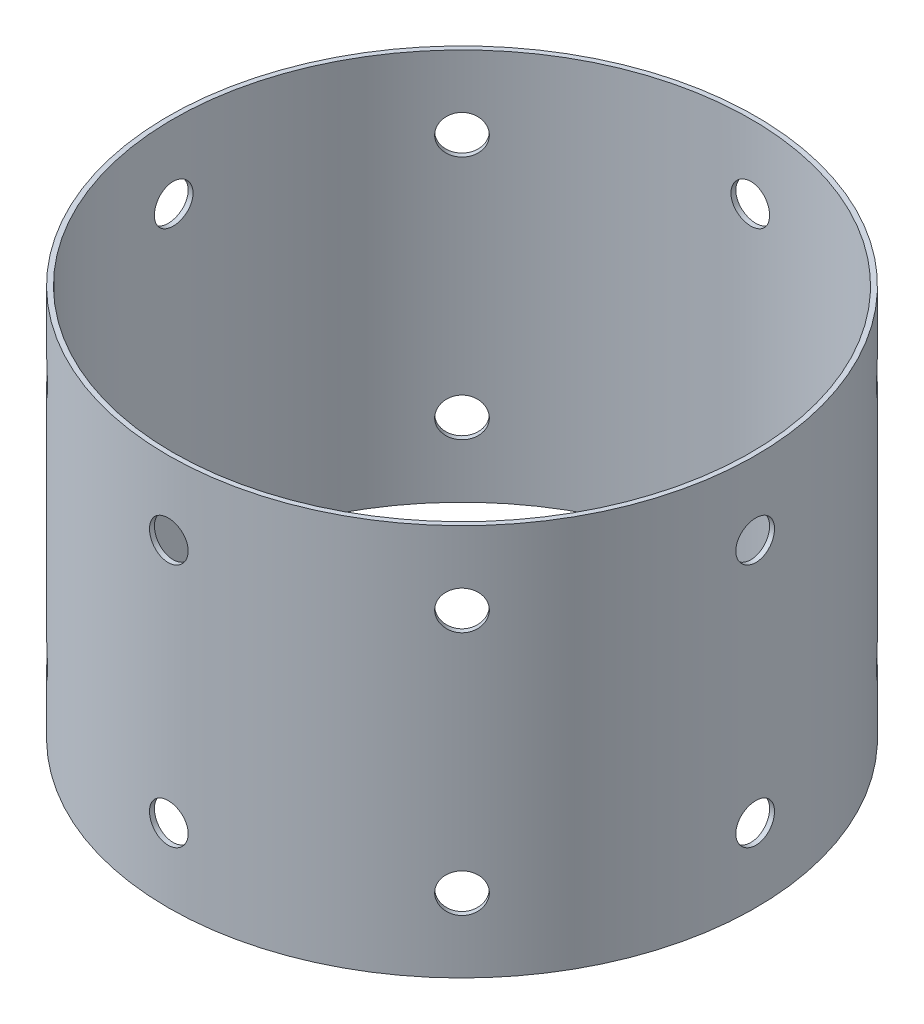
SolidWorks part; units mm, degrees
material "6061-T6 (SS)"
ref_plane "Front Plane" through (0, 0, 0) normal (0, 0, 1) x (1, 0, 0)
ref_plane "Top Plane" through (0, 0, 0) normal (0, 1, 0) x (1, 0, 0)
ref_plane "Right Plane" through (0, 0, 0) normal (1, 0, 0) x (0, 0, -1)
sketch "Sketch2" plane through (0, 0, 0) normal (0, 1, 0) x (1, 0, 0)
  circle A0 centre (0, 0) radius 74.93
  circle A1 centre (0, 0) radius 76.2
  dimension "D1" = 152.4
  dimension "D2" = 1.27
extrude "Boss-Extrude1" add sketch "Sketch2" along normal blind 101.6
sketch "Sketch3" plane through (0, 127, 0) normal (1, 0, 0) x (0, 0, -1)
  circle A0 centre (0, -44.45) radius 4.7625 construction
  circle A1 centre (0, -44.45) radius 4.7625 construction
  circle A2 centre (0, -44.45) radius 5.0165
  dimension "D1" = 0.254
extrude "LOX to Kero, LOX Side Holes" cut sketch "Sketch3" along normal up to surface (76.0347 mm away)
pattern_circular "CirPattern1" count 8 over 360 about axis through (0, 101.6, 0) along (0, 1, 0) of "LOX to Kero, LOX Side Holes"
sketch "Sketch4" plane through (0, -25.4, 0) normal (1, 0, 0) x (0, 0, 1)
  circle A0 centre (0, -44.45) radius 4.7625 construction
  circle A1 centre (0, -44.45) radius 4.7625 construction
  circle A2 centre (0, -44.45) radius 5.0165
  dimension "D1" = 0.254
extrude "LOX to Kero, Kero Side Holes" cut sketch "Sketch4" along normal up to surface (76.0347 mm away)
pattern_circular "CirPattern2" count 8 over 360 about axis through (0, 0, 0) along (0, 1, 0) of "LOX to Kero, Kero Side Holes"
sketch "Sketch5" [suppressed] plane through (0, -25.4, 0) normal (1, 0, 0) x (0, 0, 1)
  circle A0 centre (0, -44.45) radius 4.7625 construction
  circle A1 centre (0, -44.45) radius 4.7625 construction
  circle A2 centre (0, -44.45) radius 5.0165
  dimension "D1" = 0.254
extrude "N2 to LOX, LOX Side Holes" [suppressed] cut sketch "Sketch5" along normal up to surface (78.1983 mm away)
pattern_circular "CirPattern3" [suppressed] count 8 over 360
sketch "Sketch7" [suppressed] plane through (0, 0, 0) normal (1, 0, 0) x (0, 0, -1)
  line L0 (-2.3812, 327.3303) -> (2.3812, 327.3303) construction
  line L1 (0, 329.7115) -> (0, 324.949) construction
  line L2 (-2.3812, 604.52) -> (2.3812, 604.52) construction
  line L4 (0, 606.9012) -> (0, 602.1388) construction
  circle A0 centre (0, 604.52) radius 2.3812
  circle A2 centre (0, 327.3303) radius 2.3785
  spline S1 degree 3 poles (-2.3812, 327.3303) (-2.3812, 326.701) (-2.123, 326.0856) (-1.2443, 325.207) (-0.6225, 324.9494) (0.62, 324.9487) (1.2382, 325.2013) (2.1277, 326.0899) (2.381, 326.7078) (2.3815, 327.9511) (2.1241, 328.5729) (1.2467, 329.452) (0.6306, 329.7109) (-0.6258, 329.7122) (-1.2425, 329.4547) (-2.1225, 328.5761) (-2.3813, 327.9596) (-2.3812, 327.3303) (-2.3812, 326.701) (-2.123, 326.0856) knots -0.125 0 0 0 0.125 0.125 0.25 0.25 0.375 0.375 0.5 0.5 0.625 0.625 0.75 0.75 0.875 0.875 1 1 1 1.125 1.125 1.25 only from (-2.3812, 327.3303) to (-2.3812, 327.3303) construction
  spline S2 degree 3 poles (-2.3812, 327.3303) (-2.3812, 326.701) (-2.123, 326.0856) (-1.2443, 325.207) (-0.6225, 324.9494) (0.62, 324.9487) (1.2382, 325.2013) (2.1277, 326.0899) (2.381, 326.7078) (2.3815, 327.9511) (2.1241, 328.5729) (1.2467, 329.452) (0.6306, 329.7109) (-0.6258, 329.7122) (-1.2425, 329.4547) (-2.1225, 328.5761) (-2.3813, 327.9596) (-2.3812, 327.3303) (-2.3812, 326.701) (-2.123, 326.0856) knots -0.125 0 0 0 0.125 0.125 0.25 0.25 0.375 0.375 0.5 0.5 0.625 0.625 0.75 0.75 0.875 0.875 1 1 1 1.125 1.125 1.25 only from (-2.3812, 327.3303) to (-2.3812, 327.3303) construction
  spline S3 degree 3 poles (-2.3812, 604.52) (-2.3812, 603.8907) (-2.123, 603.2754) (-1.2443, 602.3967) (-0.6225, 602.1391) (0.62, 602.1384) (1.2382, 602.391) (2.1277, 603.2797) (2.381, 603.8975) (2.3815, 605.1408) (2.1241, 605.7626) (1.2467, 606.6417) (0.6306, 606.9006) (-0.6258, 606.9019) (-1.2425, 606.6444) (-2.1225, 605.7658) (-2.3813, 605.1493) (-2.3812, 604.52) (-2.3812, 603.8907) (-2.123, 603.2754) knots -0.125 0 0 0 0.125 0.125 0.25 0.25 0.375 0.375 0.5 0.5 0.625 0.625 0.75 0.75 0.875 0.875 1 1 1 1.125 1.125 1.25 only from (-2.3812, 604.52) to (-2.3812, 604.52) construction
  point P8 (0, 327.3303)
  point P17 (0, 604.52)
extrude "Cut-Extrude2" [suppressed] cut sketch "Sketch7" against normal through all both and the other way through all
pattern_circular "CirPattern4" [suppressed] count 4 over 180
sketch "Sketch9" [suppressed] plane through (0, 0, 0) normal (1, 0, 0) x (0, 0, -1)
  line L0 (0, 785.495) -> (0, 633.095) construction
  line L1 (76.2, 785.495) -> (-76.2, 785.495) construction
  circle A0 centre (0, 645.795) radius 3.175
  dimension "D3" = 6.35
  dimension "D1" = 152.4
  dimension "D2" = 12.7
extrude "Cut-Extrude3" [suppressed] cut sketch "Sketch9" against normal through all both contours A0
pattern_circular "CirPattern5" [suppressed] count 3 over 180
